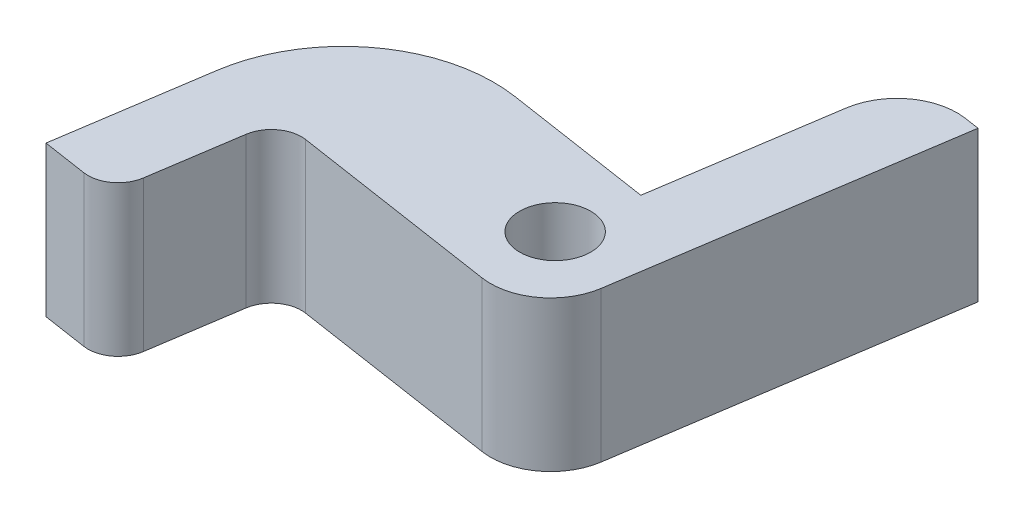
SolidWorks part; units mm, degrees
ref_plane "Front Plane" through (0, 0, 0) normal (0, 0, 1) x (1, 0, 0)
ref_plane "Top Plane" through (0, 0, 0) normal (0, 1, 0) x (1, 0, 0)
ref_plane "Right Plane" through (0, 0, 0) normal (1, 0, 0) x (0, 0, -1)
sketch "Sketch2" plane through (0, 0, 0) normal (0, 1, 0) x (1, 0, 0)
  line L4 (0, -79.6925) -> (0, -84.1375) construction
  line L9 (0, -84.1375) -> (-3.809, -84.0512) construction
  line L10 (-3.809, -84.0512) -> (-7.5917, -79.3301) construction
  line L15 (-4.4623, -82.0486) -> (-2.5535, -69.4929)
  line L16 (-2.5535, -69.4929) -> (13.1411, -71.8789)
  line L17 (17.59, -44.7) -> (-23.11, -44.7) construction
  line L18 (13.1411, -71.8789) -> (12.1867, -78.1567)
  line L19 (12.1867, -78.1567) -> (-0.369, -76.2479)
  line L20 (-0.369, -76.2479) -> (-1.3234, -82.5258)
  line L21 (-1.3234, -82.5258) -> (-4.4623, -82.0486)
  line L22 (9.525, -74.5406) -> (12.6639, -75.0178)
  line L23 (12.1867, -78.1567) -> (14.6682, -61.8343)
  line L24 (14.6682, -61.8343) -> (11.5292, -61.3571)
  line L25 (11.5292, -61.3571) -> (10.0022, -71.4017)
  line L26 (17.59, -44.7) -> (17.59, -64.7) construction
  line L27 (17.59, -64.7) -> (-23.11, -64.7) construction
  line L28 (-23.11, -44.7) -> (-23.11, -64.7) construction
  line L29 (1.4342, -56.7872) -> (4.9283, -67.0919) construction
  line L30 (10.6393, -67.0023) -> (13.8082, -56.593) construction
  line L31 (1.4342, -56.7872) -> (13.8082, -56.593) construction
  line L32 (7.59, -54.7) -> (7.6212, -56.6901) construction
  line L33 (-32, 32) -> (32, 32) construction
  line L34 (32, 32) -> (32, -32) construction
  line L35 (32, -32) -> (-32, -32) construction
  line L36 (-32, -32) -> (-32, 32) construction
  line L37 (-32, 0) -> (32, 0) construction
  line L38 (32, 32) -> (32, 0)
  line L39 (-26.685, -54.7) -> (21.165, -54.7) construction
  circle A3 centre (0, 0) radius 88.9 construction
  circle A4 centre (0, 0) radius 79.6925 construction
  circle A5 centre (0, 0) radius 84.1375 construction
  circle A8 centre (9.525, -74.5406) radius 1.5
  circle A11 centre (9.525, -74.5406) radius 13.4704 construction
  circle A12 centre (9.525, -74.5406) radius 15.875 construction
  circle A13 centre (7.59, -54.7) radius 6.5 construction
  arc A14 (4.9283, -67.0919) -> (10.6393, -67.0023) centre (7.7694, -66.1286) ccw construction
  circle A15 centre (0, 0) radius 7.9375 construction
  circle A16 centre (32, 32) radius 5.5562 construction
  circle A17 centre (-32, -32) radius 5.5562 construction
  circle A18 centre (32, -32) radius 5.5562 construction
  circle A19 centre (-32, 32) radius 5.5562 construction
  circle A20 centre (-26.685, -54.7) radius 1.5
  circle A21 centre (21.165, -54.7) radius 1.5
  point P18 (0, 0)
  point P20 (7.6787, -62.9001)
  point P21 (7.7055, -62.9029)
  point P22 (-3.175, -84.0656)
  point P33 (17.59, -54.7)
  point P40 (-2.76, -54.7)
  point P41 (8.6752, -66.1288)
  point P48 (7.7749, -66.3794)
  point P56 (-2.76, -64.7)
  point P58 (-23.11, -54.7)
  dimension "D1" = 177.8
  dimension "D2" = 9.2075
  dimension "D3" = 4.445
  dimension "D7" = 6.35
  dimension "D8" = 3.175
  dimension "D10" = 3.175
  dimension "D15" = 13
  dimension "D19" = 3
  dimension "D20" = 11.1125
  dimension "D22" = 15.875
  dimension "D25" = 3
  dimension "D26" = 3
  dimension "D4" = 50
  dimension "D5" = 3.81
  dimension "D6" = 3.175
  dimension "D9" = 6.35
  dimension "D11" = 12.7
  dimension "D12" = 12.7
  dimension "D13" = 10.16
  dimension "D14" = 3.175
  dimension "D16" = 40.7
  dimension "D17" = 20
  dimension "D18" = 10
  dimension "D21" = 64
  dimension "D23" = 8.89
  dimension "D24" = 11.43
  dimension "D27" = 47.85
  dimension "D28" = 74.5406
extrude "Boss-Extrude1" add sketch "Sketch2" along normal blind 6.35
fillet "Fillet1" radius 1.27 2 edges at (-1.3234, 3.175, 82.5258) (-0.369, 3.175, 76.2479)
fillet "Fillet2" radius 2.54 1 edges at (11.5292, 3.175, 61.3571)
fillet "Fillet3" radius 6.35 1 edges at (-2.5535, 3.175, 69.4929)
fillet "Fillet4" radius 2.54 1 edges at (12.1867, 3.175, 78.1567)
